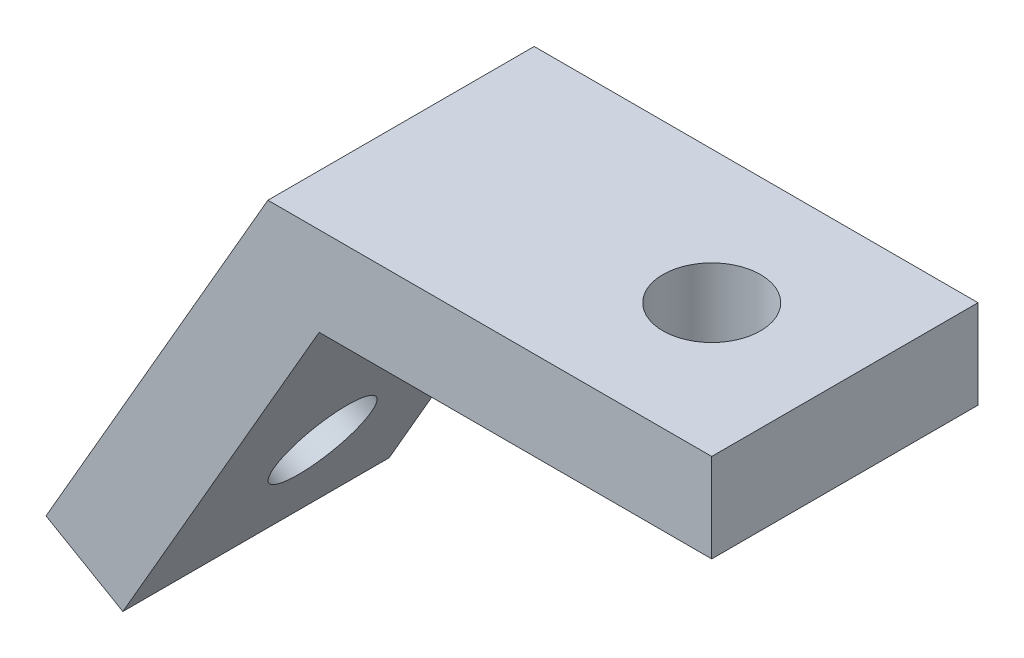
SolidWorks part; units mm, degrees
ref_plane "Front Plane" through (0, 0, 0) normal (0, 0, 1) x (1, 0, 0)
ref_plane "Top Plane" through (0, 0, 0) normal (0, 1, 0) x (1, 0, 0)
ref_plane "Right Plane" through (0, 0, 0) normal (1, 0, 0) x (0, 0, -1)
sketch "Sketch1" plane through (0, 0, 0) normal (0, 0, 1) x (1, 0, 0)
  line L0 (10.1758, 4.4712) -> (0.1758, 4.4712)
  line L1 (0.1758, 4.4712) -> (-4.8242, -4.189)
  line L2 (-4.8242, -4.189) -> (-3.0922, -5.189)
  line L3 (-3.0922, -5.189) -> (1.3305, 2.4712)
  line L4 (1.3305, 2.4712) -> (10.1758, 2.4712)
  line L5 (10.1758, 2.4712) -> (10.1758, 4.4712)
  point P2 (0, 0)
  point P8 (0, 0)
  dimension "D1" = 10
  dimension "D2" = 10
  dimension "D3" = 2
  dimension "D4" = 2
  dimension "D5" = 120
extrude "Boss-Extrude1" add sketch "Sketch1" along normal blind 6
sketch "Sketch2" plane through (0, 4.4712, 0) normal (0, 1, 0) x (1, 0, 0)
  line L0 (10.1758, 0) -> (0.1758, 0) construction
  line L1 (10.1758, -6) -> (10.1758, 0) construction
  circle A0 centre (7.1758, -3) radius 1.1
  dimension "D1" = 2.2
  dimension "D2" = 3
  dimension "D3" = 3
extrude "Cut-Extrude1" cut sketch "Sketch2" against normal blind 6
sketch "Sketch3" plane through (-1.8043, 1.0417, 0) normal (-0.866, 0.5, 0) x (0, 0, 1)
  line L0 (6, 3.9601) -> (6, -6.0399) construction
  line L1 (6, -6.0399) -> (0, -6.0399) construction
  circle A0 centre (3, -3.0399) radius 1.1
  dimension "D1" = 2.2
  dimension "D2" = 3
  dimension "D3" = 3
extrude "Cut-Extrude2" cut sketch "Sketch3" against normal blind 6
